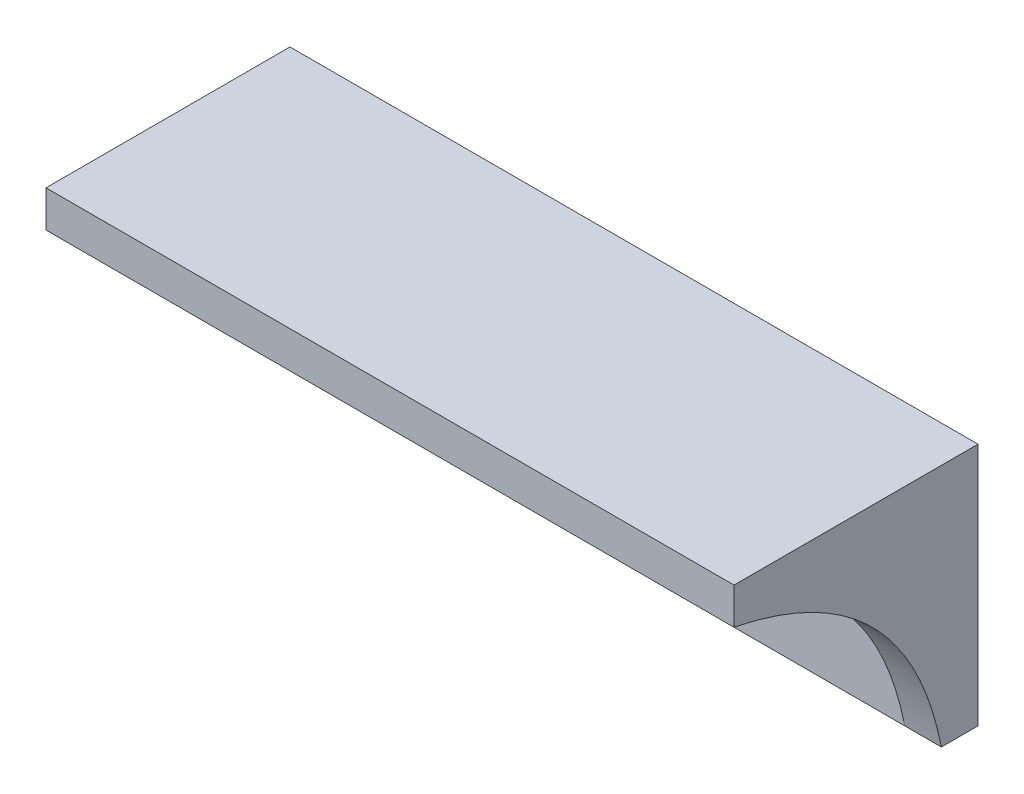
SolidWorks part; units mm, degrees
ref_plane "정면" through (0, 0, 0) normal (0, 0, 1) x (1, 0, 0)
ref_plane "윗면" through (0, 0, 0) normal (0, 1, 0) x (1, 0, 0)
ref_plane "우측면" through (0, 0, 0) normal (1, 0, 0) x (0, 0, -1)
sketch "스케치1" plane through (0, 0, 0) normal (0, 0, 1) x (1, 0, 0)
  line L1 (-28.2, 10) -> (28.2, 10)
  line L2 (-28.2, 10) -> (-28.2, -10)
  line L3 (-28.2, -10) -> (28.2, -10)
  line L4 (28.2, 10) -> (28.2, -10)
  line L5 (-28.2, 10) -> (28.2, -10) construction
  line L6 (-28.2, -10) -> (28.2, 10) construction
  point P0 (0, 0)
  dimension "D1" = 56.4
  dimension "D2" = 20
extrude "보스-돌출1" add sketch "스케치1" along normal blind 3
sketch "스케치2" plane through (0, 0, 3) normal (0, 0, 1) x (1, 0, 0)
  line L0 (-28.2, 10) -> (-28.2, -10) construction
  line L1 (-28.2, 10) -> (28.2, 10)
  line L2 (-28.2, 10) -> (-28.2, 7)
  line L3 (-28.2, 7) -> (28.2, 7)
  line L4 (28.2, 10) -> (28.2, 7)
  line L5 (28.2, -10) -> (28.2, 10) construction
  point P8 (-30, 10)
  dimension "D1" = 3
extrude "보스-돌출2" add sketch "스케치2" along normal blind 17
sketch "스케치4" plane through (-28.2, 0, 0) normal (-1, 0, 0) x (0, 0, 1)
  line L0 (3, -10) -> (3, 7)
  line L1 (3, 7) -> (20, 7)
  spline S0 degree 2 poles (3, -10) (5.8333, 4.1667) (20, 7) knots 0 0 0 1 1 1
  dimension "D1" = 5.6667
  dimension "D2" = 5.6667
extrude "보스-돌출3" add sketch "스케치4" against normal blind 3
pattern_linear "선형 패턴1" count 3 spacing 26.7 along (1, 0, 0) of "보스-돌출3"
hole_wizard "M4 여유 구멍1" positions "스케치5" profile "스케치6" hole size "M4" standard "KS" end condition through all
sketch "스케치5" plane through (0, 0, 3) normal (0, 0, 1) x (1, 0, 0)
  line L0 (-25.2, 7) -> (-25.2, -10) construction
  line L2 (-25.2, 7) -> (-1.5, 7) construction
  line L3 (1.5, 7) -> (25.2, 7) construction
  line L6 (25.2, 7) -> (25.2, -10) construction
  point P0 (-13.35, 0)
  point P2 (13.35, 0)
  dimension "D1" = 11.85
  dimension "D2" = 7
  dimension "D3" = 7
  dimension "D4" = 11.85
sketch "스케치6" plane through (-13.35, 0, 3) normal (1, 0, 0) x (0, -1, 0)
  line L0 (0, 0) -> (0, 3)
  line L1 (0, 3) -> (2.25, 3)
  line L2 (2.25, 3) -> (2.25, 0)
  line L5 (2.25, 0) -> (0, 0)
  line L11 (0, -6.35) -> (0, 107.95) construction
  dimension "관통 구멍 지름" = 4.5
  dimension "관통 구멍 깊이" = 3
